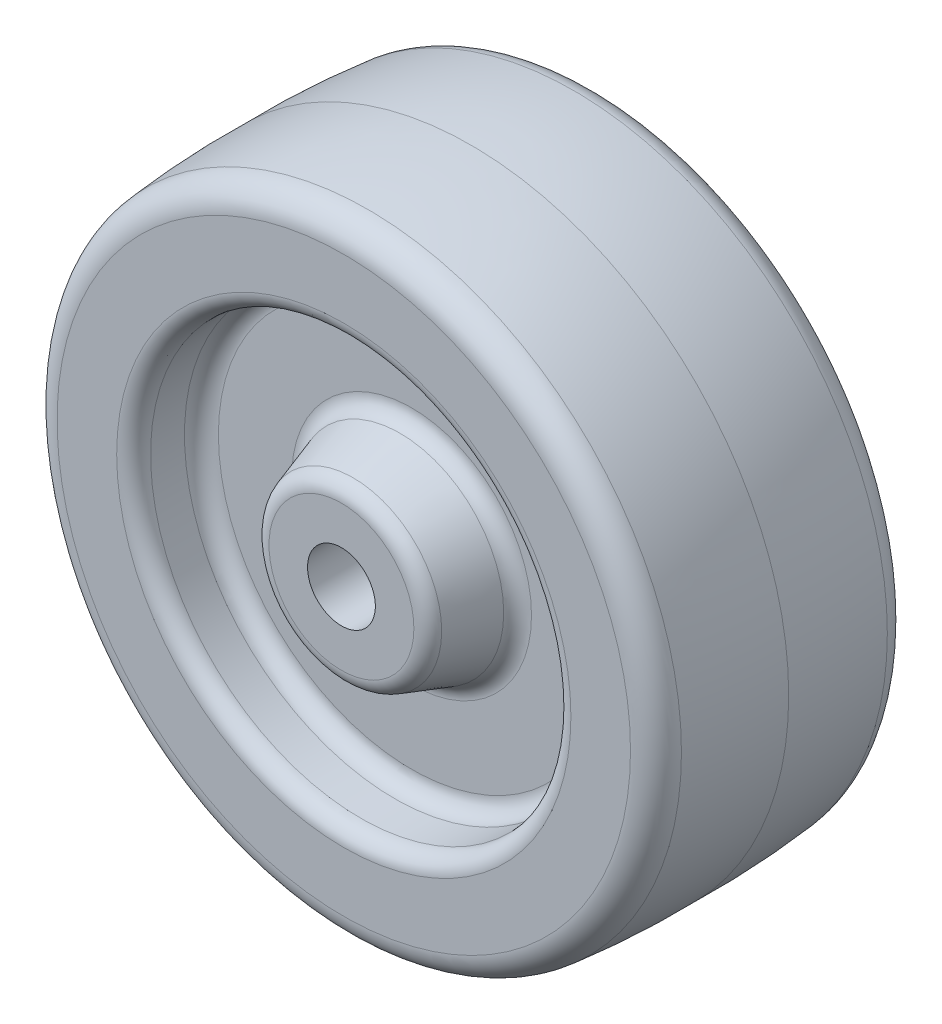
SolidWorks part; units mm, degrees
ref_plane "Front Plane" through (0, 0, 0) normal (0, 0, 1) x (1, 0, 0)
ref_plane "Top Plane" through (0, 0, 0) normal (0, 1, 0) x (1, 0, 0)
ref_plane "Right Plane" through (0, 0, 0) normal (1, 0, 0) x (0, 0, -1)
sketch "Sketch8" plane through (0, 0, 0) normal (1, 0, 0) x (0, 0, -1)
  line L0 (12.1471, -79.743) -> (0, -79.743) construction
  line L1 (-15.2777, -42.751) -> (15.2777, -42.751)
  line L2 (15, -76.5844) -> (15, -69.551)
  line L3 (0, -42.751) -> (0, -80.251) construction
  line L4 (15.2777, -51.2997) -> (15.2777, -42.751)
  line L5 (0, -42.751) -> (0, 0) construction
  line L6 (0, -37.9885) -> (0, -47.5135) construction
  line L7 (-8.3798, -55.001) -> (-13.8979, -53.2011)
  line L8 (13, -67.551) -> (9, -67.551)
  line L9 (7, -65.551) -> (7, -56.9024)
  line L10 (-7, -65.551) -> (-7, -56.9024)
  line L11 (8.3798, -55.001) -> (13.8979, -53.2011)
  line L12 (-13, -67.551) -> (-9, -67.551)
  line L13 (15.2777, -42.751) -> (0, -42.751) construction
  line L14 (-15.2777, -51.2997) -> (-15.2777, -42.751)
  line L15 (-15, -76.5844) -> (-15, -69.551)
  arc A0 (-15, -69.551) -> (-13, -67.551) centre (-13, -69.551) cw
  arc A1 (-15.2777, -51.2997) -> (-13.8979, -53.2011) centre (-13.2777, -51.2997) ccw
  arc A2 (-12.1471, -79.743) -> (-15, -76.5844) centre (-11.825, -76.5844) cw
  arc A3 (0, -80.251) -> (-12.1471, -79.743) centre (-1.8325, 21.4118) cw
  arc A4 (0, -80.251) -> (12.1471, -79.743) centre (1.8325, 21.4118) ccw
  arc A5 (12.1471, -79.743) -> (15, -76.5844) centre (11.825, -76.5844) ccw
  arc A6 (-8.3798, -55.001) -> (-7, -56.9024) centre (-9, -56.9024) cw
  arc A7 (15.2777, -51.2997) -> (13.8979, -53.2011) centre (13.2777, -51.2997) cw
  arc A8 (8.3798, -55.001) -> (7, -56.9024) centre (9, -56.9024) ccw
  arc A9 (-7, -65.551) -> (-9, -67.551) centre (-9, -65.551) cw
  arc A10 (7, -65.551) -> (9, -67.551) centre (9, -65.551) ccw
  arc A11 (15, -69.551) -> (13, -67.551) centre (13, -69.551) ccw
  point P24 (-15, -67.551)
  point P27 (-15.2777, -52.751)
  point P31 (-7, -55.451)
  point P35 (15.2777, -52.751)
  point P40 (7, -55.451)
  point P43 (-7, -67.551)
  point P46 (7, -67.551)
  point P49 (15, -67.551)
  dimension "D5" = 3.175
  dimension "D6" = 37.5
  dimension "D7" = 15
  dimension "D2" = 7
  dimension "D3" = 10
  dimension "D4" = 2
  dimension "D1" = 0.508
  dimension "D11" = 42.751
revolve "Revolve2" add sketch "Sketch8" angle 360 about L1
sketch "Esboço1" plane through (0, 0, -15.2777) normal (0, 0, -1) x (-1, 0, 0)
  circle A0 centre (0, -42.751) radius 4
  dimension "D1" = 8
extrude "Corte-extrusão1" cut sketch "Esboço1" against normal through all
